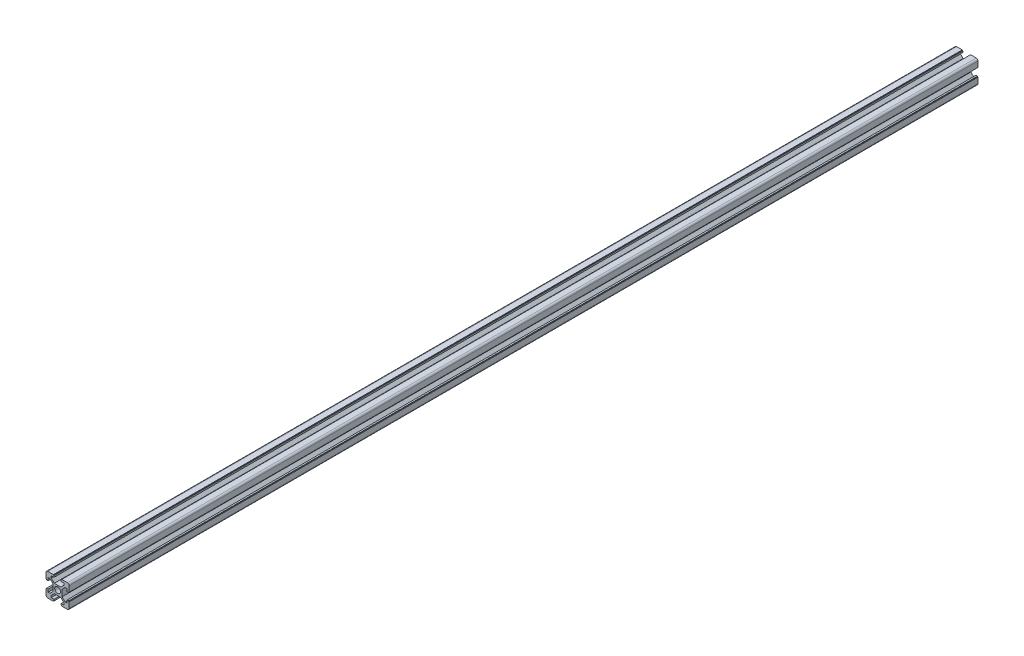
SolidWorks part; units mm, degrees
ref_plane "Front Plane" through (0, 0, 0) normal (0, 0, 1) x (1, 0, 0)
ref_plane "Top Plane" through (0, 0, 0) normal (0, 1, 0) x (1, 0, 0)
ref_plane "Right Plane" through (0, 0, 0) normal (1, 0, 0) x (0, 0, -1)
sketch "Sketch1" plane through (0, 0, 0) normal (0, 0, 1) x (1, 0, 0)
  line L0 (0, 13.3843) -> (0, -12.9126) construction
  line L1 (-14.4653, 0) -> (14.4653, 0) construction
  line L2 (2.8393, 3.9) -> (5.5, 6.5607)
  line L3 (-8.5, 10) -> (-3.6, 10)
  line L4 (-10, 8.5) -> (-10, 3.6)
  line L5 (-8.5, -10) -> (-3.6, -10)
  line L6 (10, 8.5) -> (10, 3.6)
  line L7 (-10, 10) -> (10, -10) construction
  line L8 (-10, -10) -> (10, 10) construction
  line L9 (-5.5, 8.2) -> (-3.1, 8.2)
  line L10 (-5.9626, 4.902) -> (-4.902, 5.9626) construction
  line L11 (-2.8393, 3.9) -> (-5.5, 6.5607)
  line L12 (-5.5, 8.2) -> (-5.5, 6.5607)
  line L13 (-2.8393, 3.9) -> (2.8393, 3.9)
  line L14 (5.5, 8.2) -> (5.5, 6.5607)
  line L15 (-3.1, 9.5) -> (-3.1, 8.2)
  line L16 (3.1, 9.5) -> (3.1, 8.2)
  line L17 (-3.1, 9.5) -> (3.1, 9.5) construction
  line L18 (-3.1, 9.5) -> (-3.6, 9.5)
  line L19 (-3.6, 9.5) -> (-3.6, 10)
  line L20 (3.1, 9.5) -> (3.6, 9.5)
  line L21 (3.6, 9.5) -> (3.6, 10)
  line L22 (3.6, 10) -> (8.5, 10)
  line L23 (3.1, 8.2) -> (5.5, 8.2)
  line L24 (-9.5, -3.1) -> (-9.5, -3.6)
  line L25 (-9.5, -3.6) -> (-10, -3.6)
  line L26 (-9.5, -3.1) -> (-8.2, -3.1)
  line L27 (-8.2, -3.1) -> (-8.2, -5.5)
  line L28 (-8.2, -5.5) -> (-6.5607, -5.5)
  line L29 (-3.9, -2.8393) -> (-6.5607, -5.5)
  line L30 (-3.9, 2.8393) -> (-3.9, -2.8393)
  line L31 (-3.9, 2.8393) -> (-6.5607, 5.5)
  line L32 (-8.2, 5.5) -> (-6.5607, 5.5)
  line L33 (-8.2, 5.5) -> (-8.2, 3.1)
  line L34 (-9.5, 3.1) -> (-8.2, 3.1)
  line L35 (-9.5, 3.1) -> (-9.5, 3.6)
  line L36 (-9.5, 3.6) -> (-10, 3.6)
  line L37 (-3.6, -9.5) -> (-3.6, -10)
  line L38 (-3.1, -9.5) -> (-3.6, -9.5)
  line L39 (-3.1, -9.5) -> (-3.1, -8.2)
  line L40 (-3.1, -8.2) -> (-5.5, -8.2)
  line L41 (-5.5, -8.2) -> (-5.5, -6.5607)
  line L42 (-2.8393, -3.9) -> (-5.5, -6.5607)
  line L43 (2.8393, -3.9) -> (-2.8393, -3.9)
  line L44 (2.8393, -3.9) -> (5.5, -6.5607)
  line L45 (5.5, -8.2) -> (5.5, -6.5607)
  line L46 (5.5, -8.2) -> (3.1, -8.2)
  line L47 (3.1, -9.5) -> (3.6, -9.5)
  line L48 (3.1, -9.5) -> (3.1, -8.2)
  line L49 (3.6, -9.5) -> (3.6, -10)
  line L50 (9.5, -3.6) -> (10, -3.6)
  line L51 (9.5, -3.1) -> (9.5, -3.6)
  line L52 (9.5, -3.1) -> (8.2, -3.1)
  line L53 (8.2, -5.5) -> (8.2, -3.1)
  line L54 (8.2, -5.5) -> (6.5607, -5.5)
  line L55 (3.9, -2.8393) -> (6.5607, -5.5)
  line L56 (3.9, -2.8393) -> (3.9, 2.8393)
  line L57 (3.9, 2.8393) -> (6.5607, 5.5)
  line L58 (8.2, 5.5) -> (6.5607, 5.5)
  line L59 (8.2, 3.1) -> (8.2, 5.5)
  line L60 (9.5, 3.1) -> (8.2, 3.1)
  line L61 (9.5, 3.1) -> (9.5, 3.6)
  line L62 (9.5, 3.6) -> (10, 3.6)
  line L63 (-10, -3.6) -> (-10, -8.5)
  line L64 (3.6, -10) -> (8.5, -10)
  line L65 (10, -3.6) -> (10, -8.5)
  arc A0 (8.5, 10) -> (10, 8.5) centre (8.5, 8.5) cw
  arc A1 (8.5, -10) -> (10, -8.5) centre (8.5, -8.5) ccw
  arc A2 (-10, -8.5) -> (-8.5, -10) centre (-8.5, -8.5) ccw
  arc A3 (-8.5, 10) -> (-10, 8.5) centre (-8.5, 8.5) ccw
  circle A4 centre (0, 0.2358) radius 2.5
  point P5 (0, 0)
  point P30 (-5.4323, 5.4323)
  point P38 (0, 9.5)
  dimension "D3" = 1.5
  dimension "D15" = 5
  dimension "D1" = 20
  dimension "D2" = 20
  dimension "D4" = 6.2
  dimension "D5" = 11
  dimension "D6" = 1.8
  dimension "D7" = 1.5
  dimension "D8" = 90
  dimension "D9" = 0.5
  dimension "D10" = 0.5
  dimension "D11" = 0.5
  dimension "D12" = 0.5
  dimension "D13" = 6.1
  dimension "D14" = 45
extrude "Boss-Extrude1" add sketch "Sketch1" along normal blind 786
